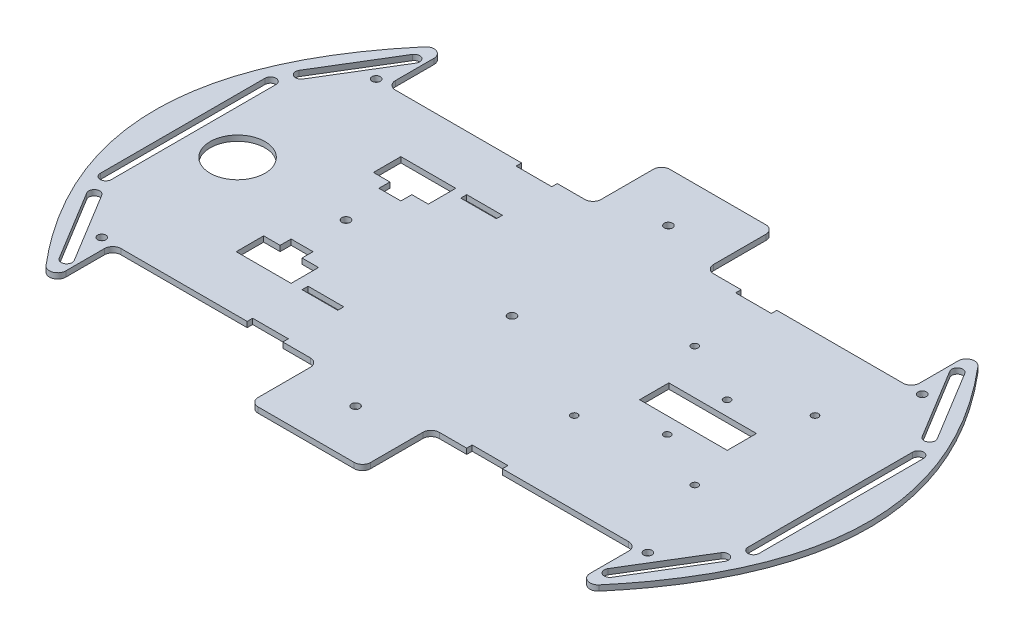
SolidWorks part; units mm, degrees
ref_plane "Front Plane" through (0, 0, 0) normal (0, 0, 1) x (1, 0, 0)
ref_plane "Top Plane" through (0, 0, 0) normal (0, 1, 0) x (1, 0, 0)
ref_plane "Right Plane" through (0, 0, 0) normal (1, 0, 0) x (0, 0, -1)
sketch "Sketch1" plane through (0, 0, 0) normal (0, 1, 0) x (1, 0, 0)
  line L0 (-95.5, 75) -> (-95.5, -75) construction
  line L1 (-130, 75) -> (130, 75)
  line L2 (-130, 75) -> (-130, -75)
  line L3 (-130, -75) -> (130, -75)
  line L4 (130, 75) -> (130, -75)
  line L5 (-130, 75) -> (130, -75) construction
  line L6 (-130, -75) -> (130, 75) construction
  line L7 (0, 83.5132) -> (0, -90.0376) construction
  line L8 (-95.5, 75) -> (-95.5, 50)
  line L9 (-95.5, 50) -> (-20.5, 50)
  line L10 (-20.5, 50) -> (-20.5, 75)
  line L11 (-20.5, 75) -> (0, 75)
  line L12 (20.5, 50) -> (20.5, 75)
  line L13 (95.5, 75) -> (95.5, 50)
  line L14 (95.5, 50) -> (20.5, 50)
  line L16 (95.5, -75) -> (95.5, -50)
  line L17 (95.5, -50) -> (20.5, -50)
  line L18 (20.5, -50) -> (20.5, -75)
  line L19 (-20.5, -50) -> (-20.5, -75)
  line L20 (-95.5, -50) -> (-20.5, -50)
  line L21 (-95.5, -75) -> (-95.5, -50)
  line L22 (-46.5, 50) -> (-46.5, 48)
  line L23 (-46.5, 48) -> (-33.5, 48)
  line L24 (-33.5, 48) -> (-33.5, 50)
  line L26 (-46.5, 30) -> (-33.5, 30)
  line L29 (-46.5, 30) -> (-46.5, 27.8038)
  line L30 (-46.5, 27.8038) -> (-33.5, 27.8038)
  line L31 (-33.5, 27.8038) -> (-33.5, 30)
  line L32 (-33.5, -27.8038) -> (-33.5, -30)
  line L33 (-46.5, -30) -> (-46.5, -27.8038)
  line L34 (-46.5, -30) -> (-33.5, -30)
  line L35 (-46.5, -27.8038) -> (-33.5, -27.8038)
  line L44 (-50.5, 30) -> (-70.5, 30)
  line L45 (-70.5, 30) -> (-70.5, 20)
  line L46 (-70.5, 20) -> (-64.5, 20)
  line L47 (-50.5, 30) -> (-50.5, 20)
  line L48 (-50.5, 20) -> (-56.5, 20)
  line L49 (-64.5, 20) -> (-64.5, 16)
  line L50 (-56.5, 20) -> (-56.5, 16)
  line L51 (-56.5, 16) -> (-64.5, 16)
  line L52 (-56.5, -20) -> (-56.5, -16)
  line L53 (-50.5, -20) -> (-56.5, -20)
  line L54 (-50.5, -30) -> (-50.5, -20)
  line L55 (-50.5, -30) -> (-70.5, -30)
  line L56 (-70.5, -30) -> (-70.5, -20)
  line L57 (-70.5, -20) -> (-64.5, -20)
  line L58 (-64.5, -20) -> (-64.5, -16)
  line L59 (-56.5, -16) -> (-64.5, -16)
  line L76 (-70.5, 25) -> (-169.0961, 25) construction
  line L77 (-120, 85.6828) -> (-120, -92.3992) construction
  line L78 (-118, 92.3992) -> (-118, -92.3992) construction
  line L79 (-118, 30) -> (-118, -30) construction
  line L80 (-116, 30) -> (-116, -30)
  line L81 (-120, 30) -> (-120, -30)
  line L82 (-118, 32) -> (-95.5, 69)
  line L83 (-114.5437, 37.6837) -> (-98.9563, 63.3163) construction
  line L86 (0, 75) -> (0, 57)
  line L87 (-116.2526, 38.7228) -> (-100.6651, 64.3555)
  line L88 (-112.8349, 36.6445) -> (-97.2474, 62.2772)
  line L89 (-114.5437, -37.6837) -> (-98.9563, -63.3163) construction
  line L90 (-116.2526, -38.7228) -> (-100.6651, -64.3555)
  line L91 (-112.8349, -36.6445) -> (-97.2474, -62.2772)
  line L92 (114.5437, -37.6837) -> (98.9563, -63.3163) construction
  line L93 (116.2526, -38.7228) -> (100.6651, -64.3555)
  line L94 (112.8349, -36.6445) -> (97.2474, -62.2772)
  line L95 (118, 30) -> (118, -30) construction
  line L96 (116, 30) -> (116, -30)
  line L97 (120, 30) -> (120, -30)
  line L98 (114.5437, 37.6837) -> (98.9563, 63.3163) construction
  line L99 (116.2526, 38.7228) -> (100.6651, 64.3555)
  line L100 (112.8349, 36.6445) -> (97.2474, 62.2772)
  line L101 (-100, 0) -> (-100, 80.5994) construction
  line L102 (-33.5, -48) -> (-33.5, -50)
  line L107 (-46.5, -48) -> (-33.5, -48)
  line L108 (-46.5, -50) -> (-46.5, -48)
  line L109 (46.5, -50) -> (46.5, -48)
  line L110 (46.5, -48) -> (33.5, -48)
  line L111 (33.5, -48) -> (33.5, -50)
  line L112 (33.5, 48) -> (33.5, 50)
  line L113 (46.5, 48) -> (33.5, 48)
  line L114 (46.5, 50) -> (46.5, 48)
  line L126 (49.722, 7.4143) -> (81.6695, 7.4143)
  line L127 (49.722, 7.4143) -> (49.722, -3.2348)
  line L128 (49.722, -3.2348) -> (81.6695, -3.2348)
  line L129 (81.6695, 7.4143) -> (81.6695, -3.2348)
  circle A0 centre (-100, 0) radius 10
  circle A2 centre (-99.5, 50) radius 1.5
  circle A3 centre (-99.5, -50) radius 1.5
  circle A4 centre (99.5, -50) radius 1.5
  circle A5 centre (99.5, 50) radius 1.5
  arc A6 (-116, 30) -> (-120, 30) centre (-118, 30) ccw
  arc A7 (-120, -30) -> (-116, -30) centre (-118, -30) ccw
  circle A10 centre (0, 57) radius 1.5
  circle A11 centre (0, -57) radius 1.5
  arc A12 (-116.2526, 38.7228) -> (-112.8349, 36.6445) centre (-114.5437, 37.6837) ccw
  arc A13 (-97.2474, 62.2772) -> (-100.6651, 64.3555) centre (-98.9563, 63.3163) ccw
  arc A14 (-116.2526, -38.7228) -> (-112.8349, -36.6445) centre (-114.5437, -37.6837) cw
  arc A15 (-97.2474, -62.2772) -> (-100.6651, -64.3555) centre (-98.9563, -63.3163) cw
  arc A16 (116.2526, -38.7228) -> (112.8349, -36.6445) centre (114.5437, -37.6837) ccw
  arc A17 (97.2474, -62.2772) -> (100.6651, -64.3555) centre (98.9563, -63.3163) ccw
  arc A18 (116, 30) -> (120, 30) centre (118, 30) cw
  arc A19 (120, -30) -> (116, -30) centre (118, -30) cw
  arc A20 (116.2526, 38.7228) -> (112.8349, 36.6445) centre (114.5437, 37.6837) cw
  arc A21 (97.2474, 62.2772) -> (100.6651, 64.3555) centre (98.9563, 63.3163) cw
  circle A22 centre (0, 0) radius 1.5
  circle A24 centre (-60.5, 0) radius 1.5
  circle A35 centre (42.8293, 23.7394) radius 1.25
  circle A36 centre (86.6699, 23.7394) radius 1.25
  circle A37 centre (86.6699, -20.1012) radius 1.25
  circle A38 centre (42.8293, -20.1012) radius 1.25
  circle A39 centre (65.6958, -9.151) radius 1.25
  circle A40 centre (65.6958, 12.6732) radius 1.25
  spline S0 degree 2 poles (-95.5, 75) (-164.5, 0) (-95.5, -75) knots 0 0 0 1 1 1
  spline S1 degree 2 poles (95.5, 75) (164.5, 0) (95.5, -75) knots 0 0 0 1 1 1
  point P0 (0, 0)
  point P21 (0, 0)
  point P22 (0, 0)
  point P41 (0, 0)
  point P42 (0, 0)
  point P43 (65.6958, 12.6732)
  point P44 (0, 0)
  point P45 (65.6958, -9.151)
  point P75 (0, 0)
  point P81 (0, 0)
  point P82 (0, 0)
  point P99 (-118, 0)
  point P102 (-118, 0)
  point P111 (-106.75, 50.5)
  point P122 (-106.75, -50.5)
  point P129 (106.75, -50.5)
  point P136 (118, 0)
  point P143 (106.75, 50.5)
  dimension "D11" = 20
  dimension "D20" = 3
  dimension "D30" = 3
  dimension "D31" = 3
  dimension "D1" = 260
  dimension "D2" = 150
  dimension "D3" = 34.5
  dimension "D4" = 25
  dimension "D5" = 75
  dimension "D6" = 2
  dimension "D7" = 13
  dimension "D8" = 13
  dimension "D9" = 20
  dimension "D10" = 20.1962
  dimension "D12" = 30
  dimension "D13" = 4
  dimension "D14" = 20
  dimension "D15" = 10
  dimension "D16" = 6
  dimension "D17" = 6
  dimension "D18" = 10
  dimension "D19" = 4
  dimension "D21" = 4
  dimension "D22" = 10
  dimension "D23" = 12
  dimension "D24" = 4
  dimension "D25" = 60
  dimension "D26" = 6
  dimension "D27" = 4
  dimension "D28" = 30
  dimension "D29" = 18
extrude "Boss-Extrude1" add sketch "Sketch1" along normal blind 2
fillet "Fillet1" radius 3 16 edges at (-20.5, 1, -50) (-20.5, 1, -75) (95.5, 1, -75) (20.5, 1, -75) (20.5, 1, -50) (95.5, 1, -50) (95.5, 1, 75) (95.5, 1, 50) (20.5, 1, 50) (20.5, 1, 75) (-20.5, 1, 75) (-20.5, 1, 50) (-95.5, 1, 50) (-95.5, 1, -50) (-95.5, 1, -75) (-95.5, 1, 75)
